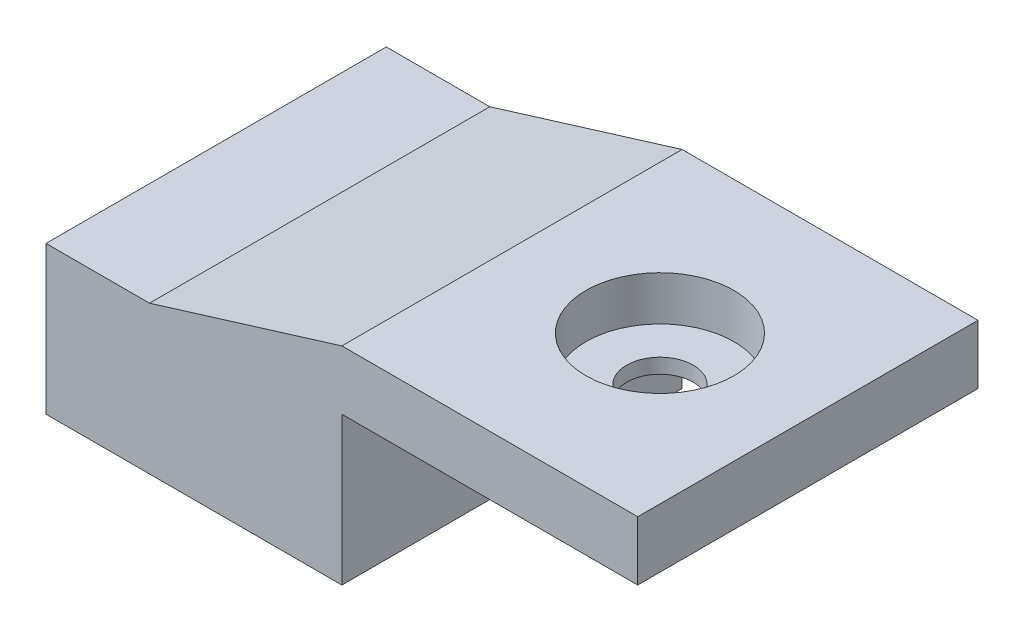
SolidWorks part; units mm, degrees
material "ABS generico"
ref_plane "Piano frontale" through (0, 0, 0) normal (0, 0, 1) x (1, 0, 0)
ref_plane "Piano superiore" through (0, 0, 0) normal (0, 1, 0) x (1, 0, 0)
ref_plane "Piano destro" through (0, 0, 0) normal (1, 0, 0) x (0, 0, -1)
sketch "Schizzo1" plane through (0, 0, 0) normal (0, 0, 1) x (1, 0, 0)
  line L0 (0, 0) -> (20, 0)
  line L1 (20, 0) -> (20, 10)
  line L2 (20, 10) -> (40, 10)
  line L3 (40, 10) -> (40, 14)
  line L4 (40, 14) -> (20, 14)
  line L6 (0, 10) -> (0, 0)
  line L7 (0, 10) -> (20, 10) construction
  line L8 (0, 10) -> (7, 10)
  line L9 (7, 10) -> (20, 14)
  line L10 (20, 10) -> (20, 14) construction
  dimension "D1" = 10
  dimension "D2" = 20
  dimension "D3" = 7
  dimension "D4" = 4
  dimension "D5" = 20
extrude "Estrusione-Estrusione1" add sketch "Schizzo1" along normal blind 23
hole_wizard "Foro per Vite M4-1" positions "Schizzo3D1" profile "Schizzo2" hole size "M4" standard "ISO"
sketch3d "Schizzo3D1"
  line L0 (0, 3.8862, 5) -> (0, 3.8862, 18) construction
  line L2 (0, 10, 23) -> (0, 10, 0) construction
  line L3 (0, 10, 0) -> (0, 0, 0) construction
  point P0 (0, 3.8862, 5)
  point P2 (0, 3.8862, 18)
  dimension "D1" = 13
  dimension "D2" = 6.1138
  dimension "D3" = 5
sketch "Schizzo2" plane through (0, 3.8862, 5) normal (0, 1, 0) x (0, 0, 1)
  line L0 (0, 0) -> (0, 11.6824)
  line L1 (0, 11.6824) -> (2.8, 10)
  line L2 (2.8, 10) -> (2.8, 0)
  line L5 (2.8, 0) -> (0, 0)
  line L10 (0, 11.6824) -> (-2.8, 10) construction
  line L11 (0, -6.35) -> (0, 107.95) construction
  dimension "Hole Dia." = 5.6
  dimension "Hole Depth" = 10
  dimension "Drill Angle" = 118
sketch "Schizzo3" plane through (0, 14, 0) normal (0, 1, 0) x (1, 0, 0)
  line L0 (20, 0) -> (40, -23) construction
  point P0 (30, -11.5)
  point P11 (30, -11.5)
hole_wizard "Foro lamato per Bullone M5 a testa esagonale-1" positions "Schizzo3" profile "Schizzo4" counterbore size "M5" standard "ISO"
sketch "Schizzo4" plane through (30, 14, 11.5) normal (1, 0, 0) x (0, 0, 1)
  line L0 (0, 0) -> (0, 11.3519)
  line L1 (0, 11.3519) -> (2.25, 10)
  line L2 (2.25, 10) -> (2.25, 3)
  line L3 (2.25, 3) -> (5, 3)
  line L4 (5, 3) -> (5, 0)
  line L5 (5, 0) -> (0, 0)
  line L10 (0, 11.3519) -> (-2.25, 10) construction
  line L11 (0, -6.35) -> (0, 107.95) construction
  dimension "Hole Dia." = 4.5
  dimension "Hole Depth" = 10
  dimension "C'Bore Dia." = 10
  dimension "C'Bore Depth" = 3
  dimension "Drill Angle" = 118
